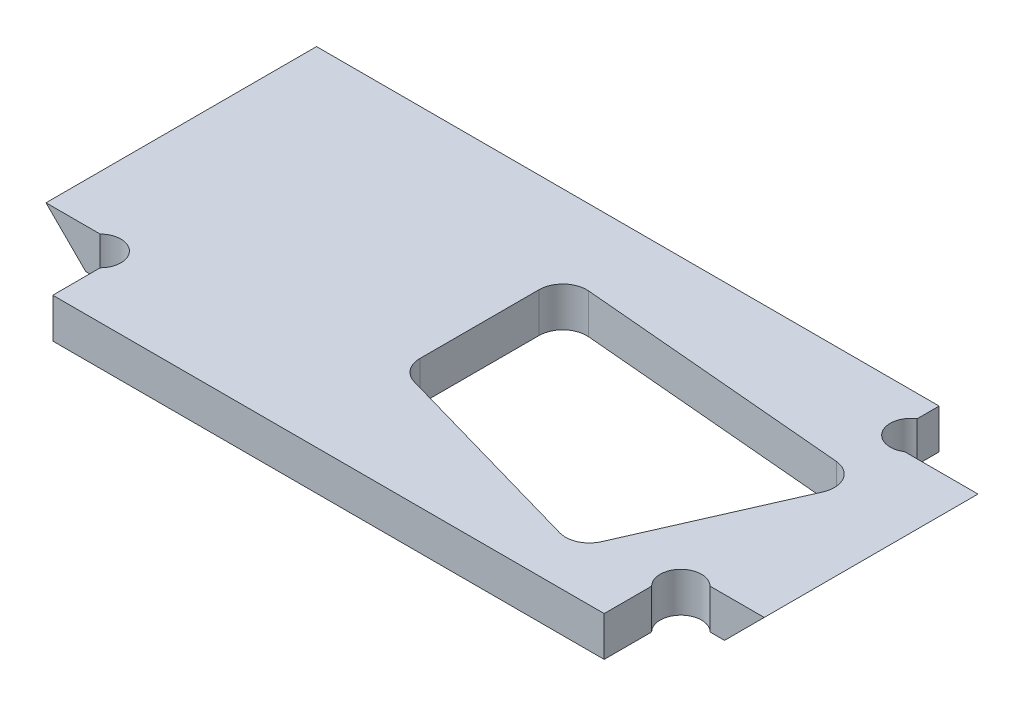
SolidWorks part; units mm, degrees
ref_plane "Front Plane" through (0, 0, 0) normal (0, 0, 1) x (1, 0, 0)
ref_plane "Top Plane" through (0, 0, 0) normal (0, 1, 0) x (1, 0, 0)
ref_plane "Right Plane" through (0, 0, 0) normal (1, 0, 0) x (0, 0, -1)
sketch "Sketch1" plane through (0, 0, 0) normal (0, 1, 0) x (1, 0, 0)
  line L0 (0, 0) -> (0, 77.1308) construction
  line L1 (-114.808, 77.1308) -> (114.808, 77.1308)
  line L2 (-114.808, 77.1308) -> (-114.808, -33.8672)
  line L3 (-114.808, -33.8672) -> (114.808, -33.8672)
  line L4 (114.808, 77.1308) -> (114.808, -33.8672)
  line L5 (-89.3342, -34.2482) -> (89.6118, -34.2482) construction
  line L6 (84.5829, 77.5118) -> (-115.7278, 77.5118) construction
  dimension "D1" = 229.616
  dimension "D2" = 0.381
  dimension "D3" = 0.381
extrude "Boss-Extrude1" add sketch "Sketch1" along normal blind 12.7
draft "Draft1" type of draft neutral plane draft angle 45 faces to draft 2 face at (-114.808, 6.35, -21.6318) face at (114.808, 6.35, -21.6318) neutral plane through (0, 12.7, 0) neutral plane normal (0, 1, 0) reverse direction yes parameters "D1"=45
sketch "Sketch2" plane through (0, 12.7, 0) normal (0, 1, 0) x (1, 0, 0)
  line L0 (-114.808, -9.3562) -> (-97.4775, -9.3562)
  line L1 (-114.808, 77.1308) -> (-114.808, -33.8672) construction
  line L2 (-88.138, -18.6956) -> (-88.138, -33.8672)
  line L3 (-114.808, -33.8672) -> (114.808, -33.8672) construction
  line L4 (-88.138, -33.8672) -> (-114.808, -33.8672)
  line L5 (-114.808, -33.8672) -> (-114.808, -9.3562)
  line L6 (0, 77.1308) -> (0, 0) construction
  line L7 (114.808, 77.1308) -> (-114.808, 77.1308) construction
  line L8 (-101.9667, -9.7372) -> (-128.9075, -9.7372) construction
  line L9 (-88.138, -18.6956) -> (-88.138, -9.3562) construction
  line L10 (-88.138, -9.3562) -> (-97.4775, -9.3562) construction
  line L11 (88.138, -9.3562) -> (97.4775, -9.3562) construction
  line L12 (88.138, -18.6956) -> (88.138, -9.3562) construction
  line L13 (114.808, -33.8672) -> (114.808, -9.3562)
  line L14 (88.138, -33.8672) -> (114.808, -33.8672)
  line L15 (88.138, -18.6956) -> (88.138, -33.8672)
  line L16 (114.808, -9.3562) -> (97.4775, -9.3562)
  line L17 (114.808, -33.8672) -> (114.808, 77.1308) construction
  line L18 (84.2246, 77.1308) -> (114.808, 77.1308)
  line L19 (84.2246, 77.1308) -> (84.2246, 70.0996)
  line L20 (91.3366, 58.9698) -> (114.808, 58.9698)
  line L21 (114.808, 77.1308) -> (114.808, 58.9698)
  line L22 (84.6056, 59.3508) -> (84.6056, 72.0508) construction
  line L23 (102.3856, 59.3508) -> (84.6056, 59.3508) construction
  line L24 (84.2246, 70.0996) -> (84.2246, 58.9698) construction
  line L25 (84.2246, 58.9698) -> (91.3366, 58.9698) construction
  arc A0 (-88.138, -18.6956) -> (-97.4775, -9.3562) centre (-92.8077, -14.0259) ccw
  arc A1 (88.138, -18.6956) -> (97.4775, -9.3562) centre (92.8077, -14.0259) cw
  arc A2 (84.2246, 70.0996) -> (91.3366, 58.9698) centre (87.7806, 64.5347) ccw
  dimension "D2" = 6.604
  dimension "D6" = 6.604
  dimension "D1" = 0.381
  dimension "D3" = 26.67
  dimension "D4" = 0.381
  dimension "D5" = 0.381
  dimension "D7" = 7.112
extrude "Cut-Extrude1" cut sketch "Sketch2" against normal through all
sketch "Sketch3" plane through (0, 12.7, 0) normal (0, 1, 0) x (1, 0, 0)
  line L0 (-3.6538, 52.9718) -> (83.0971, 45.3808)
  line L1 (89.408, 34.7221) -> (67.818, -14.367)
  line L2 (58.7533, -18.6272) -> (-6.4075, -0.0471)
  line L3 (-11.938, 7.2808) -> (-11.938, 45.3808)
  line L4 (-11.938, 26.3308) -> (-49.9785, 26.3308) construction
  line L5 (84.2246, 77.1308) -> (-114.808, 77.1308) construction
  line L6 (88.138, -18.6956) -> (88.138, -33.8672) construction
  line L7 (114.808, -9.3562) -> (114.808, 58.9698) construction
  line L8 (-88.138, -33.8672) -> (88.138, -33.8672) construction
  arc A1 (67.818, -14.367) -> (58.7533, -18.6272) centre (60.8428, -11.2992) cw
  arc A2 (-6.4075, -0.0471) -> (-11.938, 7.2808) centre (-4.318, 7.2808) cw
  arc A3 (-3.6538, 52.9718) -> (-11.938, 45.3808) centre (-4.318, 45.3808) ccw
  arc A4 (83.0971, 45.3808) -> (89.408, 34.7221) centre (82.4328, 37.7899) cw
  dimension "D1" = 11.938
  dimension "D2" = 7.62
  dimension "D3" = 31.75
  dimension "D4" = 38.1
  dimension "D5" = 50.8
  dimension "D6" = 20.32
  dimension "D7" = 25.4
  dimension "D8" = 15.24
extrude "Cut-Extrude2" cut sketch "Sketch3" against normal through all
